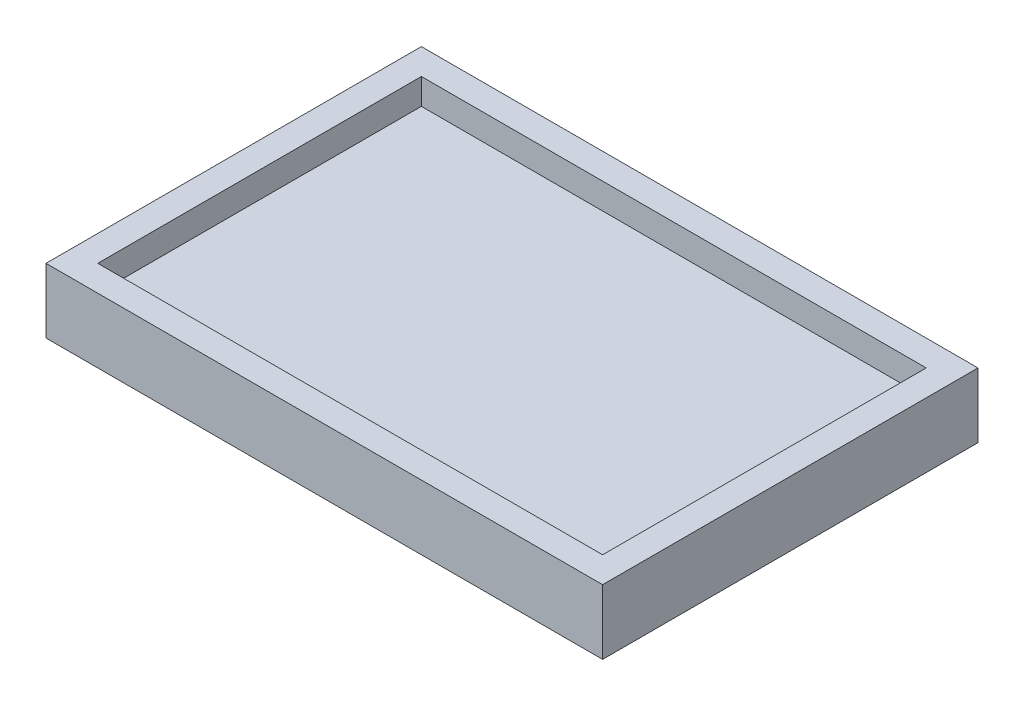
SolidWorks part; units mm, degrees
ref_plane "Plan de face" through (0, 0, 0) normal (0, 0, 1) x (1, 0, 0)
ref_plane "Plan de dessus" through (0, 0, 0) normal (0, 1, 0) x (1, 0, 0)
ref_plane "Plan de droite" through (0, 0, 0) normal (1, 0, 0) x (0, 0, -1)
sketch "Esquisse1" plane through (0, 0, 0) normal (0, 1, 0) x (1, 0, 0)
  line L5 (-21.5, 14.5) -> (21.5, 14.5)
  line L6 (-21.5, 14.5) -> (-21.5, -14.5)
  line L7 (-21.5, -14.5) -> (21.5, -14.5)
  line L8 (21.5, 14.5) -> (21.5, -14.5)
  dimension "D1" = 43
  dimension "D2" = 21.5
  dimension "D3" = 29
  dimension "D4" = 14.5
extrude "Boss.-Extru.1" add sketch "Esquisse1" along normal blind 5
sketch "Esquisse3" plane through (0, 5, 0) normal (0, 1, 0) x (1, 0, 0)
  line L8 (-19.5, 12.5) -> (-19.5, -12.5)
  line L9 (-19.5, -12.5) -> (19.5, -12.5)
  line L10 (19.5, -12.5) -> (19.5, 12.5)
  line L11 (19.5, 12.5) -> (-19.5, 12.5)
  line L12 (-19.5, 12.5) -> (-19.5, -12.5)
  line L13 (-19.5, -12.5) -> (19.5, -12.5)
  line L14 (19.5, -12.5) -> (19.5, 12.5)
  line L15 (19.5, 12.5) -> (-19.5, 12.5)
  dimension "D1" = 2
extrude "Enlèv. mat.-Extru.2" cut sketch "Esquisse3" against normal blind 2
